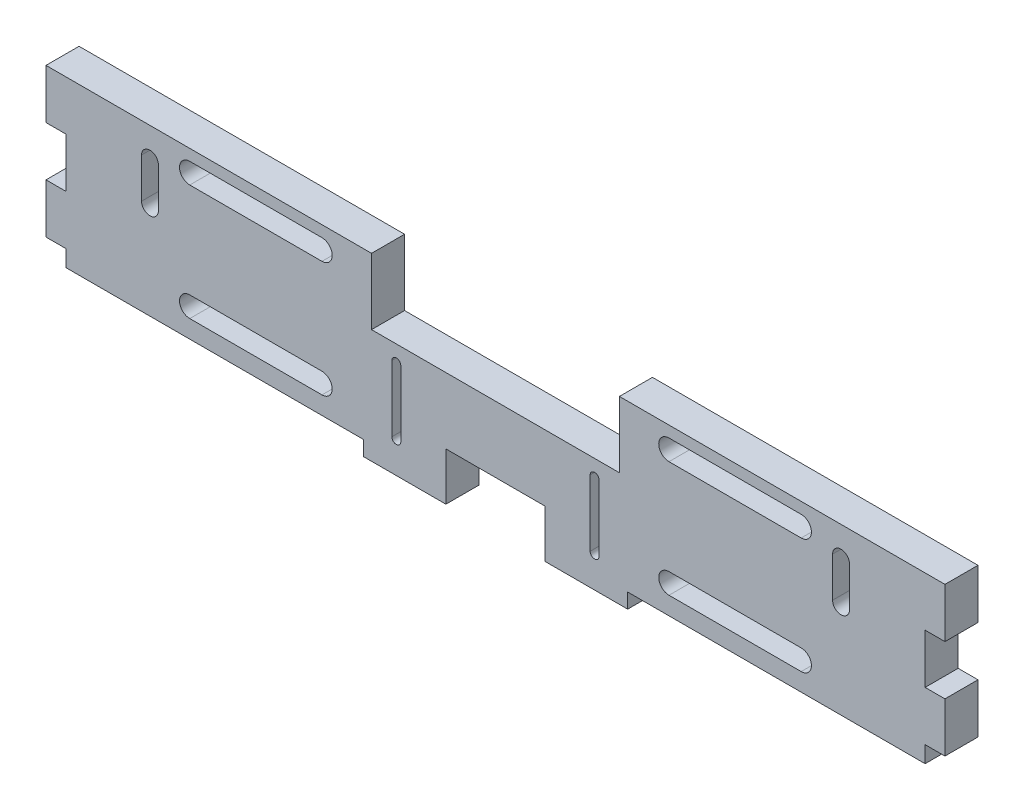
SolidWorks part; units mm, degrees
ref_plane "前基準面" through (0, 0, 0) normal (0, 0, 1) x (1, 0, 0)
ref_plane "上基準面" through (0, 0, 0) normal (0, 1, 0) x (1, 0, 0)
ref_plane "右基準面" through (0, 0, 0) normal (1, 0, 0) x (0, 0, -1)
sketch "草圖1" plane through (0, 0, 0) normal (0, 0, 1) x (1, 0, 0)
  line L0 (136, -22.5) -> (136, -7.5)
  line L1 (136, 22.5) -> (-136, 22.5)
  line L2 (130, 7.5) -> (130, -7.5)
  line L3 (130, -27.5) -> (-130, -27.5)
  line L4 (-130, 7.5) -> (-130, -7.5)
  line L5 (0, -27.5) -> (0, 22.5) construction
  line L6 (130, 0) -> (-130, 0) construction
  line L9 (-130, 7.5) -> (-136, 7.5)
  line L10 (-136, 22.5) -> (-136, 7.5)
  line L14 (-136, -22.5) -> (-136, -7.5)
  line L15 (130, -7.5) -> (136, -7.5)
  line L16 (130, 7.5) -> (136, 7.5)
  line L17 (136, 22.5) -> (136, 7.5)
  line L18 (-136, -22.5) -> (-130, -22.5)
  line L19 (-130, -22.5) -> (-130, -27.5)
  line L20 (-136, -7.5) -> (-130, -7.5)
  line L21 (130, -22.5) -> (130, -27.5)
  line L22 (130, -22.5) -> (136, -22.5)
  line L23 (-30, -22.5) -> (-30, -2.5) construction
  line L24 (-31.35, -22.5) -> (-31.35, -2.5)
  line L25 (-28.65, -22.5) -> (-28.65, -2.5)
  line L26 (30, -22.5) -> (30, -2.5) construction
  line L27 (31.35, -22.5) -> (31.35, -2.5)
  line L28 (28.65, -22.5) -> (28.65, -2.5)
  arc A0 (-31.35, -22.5) -> (-28.65, -22.5) centre (-30, -22.5) ccw
  arc A1 (-28.65, -2.5) -> (-31.35, -2.5) centre (-30, -2.5) ccw
  arc A2 (31.35, -22.5) -> (28.65, -22.5) centre (30, -22.5) cw
  arc A3 (28.65, -2.5) -> (31.35, -2.5) centre (30, -2.5) cw
  point P0 (0, 0)
  point P8 (0, 0)
  point P13 (-136, -15)
  point P14 (136, -15)
  point P24 (-30, -12.5)
  point P31 (30, -12.5)
  point P36 (0, 0)
  dimension "D8" = 1.35
  dimension "D1" = 260
  dimension "D2" = 6
  dimension "D3" = 15
  dimension "D4" = 6
  dimension "D5" = 50
  dimension "D6" = 5
  dimension "D7" = 20
  dimension "D9" = 5
  dimension "D10" = 30
extrude "填料-伸長1" add sketch "草圖1" along normal blind 10
sketch "草圖2" plane through (0, 0, 10) normal (0, 0, 1) x (1, 0, 0)
  line L0 (-92.5, 16) -> (-52.5, 16) construction
  line L1 (-92.5, 19.1) -> (-52.5, 19.1)
  line L2 (-92.5, 12.9) -> (-52.5, 12.9)
  line L3 (-92.5, -19) -> (-52.5, -19) construction
  line L4 (-92.5, -15.9) -> (-52.5, -15.9)
  line L5 (-92.5, -22.1) -> (-52.5, -22.1)
  line L6 (0, 61.8937) -> (0, -44.053) construction
  line L7 (-130, -27.5) -> (130, -27.5) construction
  line L8 (52.5, 16) -> (92.5, 16) construction
  line L9 (52.5, 19.1) -> (92.5, 19.1)
  line L10 (52.5, 12.9) -> (92.5, 12.9)
  line L11 (52.5, -19) -> (92.5, -19) construction
  line L12 (52.5, -15.9) -> (92.5, -15.9)
  line L13 (52.5, -22.1) -> (92.5, -22.1)
  arc A0 (-92.5, 19.1) -> (-92.5, 12.9) centre (-92.5, 16) ccw
  arc A1 (-52.5, 12.9) -> (-52.5, 19.1) centre (-52.5, 16) ccw
  arc A2 (-92.5, -15.9) -> (-92.5, -22.1) centre (-92.5, -19) ccw
  arc A3 (-52.5, -22.1) -> (-52.5, -15.9) centre (-52.5, -19) ccw
  arc A4 (52.5, 19.1) -> (52.5, 12.9) centre (52.5, 16) ccw
  arc A5 (92.5, 12.9) -> (92.5, 19.1) centre (92.5, 16) ccw
  arc A6 (52.5, -15.9) -> (52.5, -22.1) centre (52.5, -19) ccw
  arc A7 (92.5, -22.1) -> (92.5, -15.9) centre (92.5, -19) ccw
  point P2 (-72.5, 16)
  point P7 (-72.5, -19)
  point P22 (72.5, 16)
  point P27 (72.5, -19)
  point P37 (-95.6, -19)
  point P38 (49.4, -19)
  dimension "D3" = 3.1
  dimension "D1" = 35
  dimension "D2" = 5.4
  dimension "D4" = 40
  dimension "D6" = 145
  dimension "D5" = 2
extrude "除料-伸長1" cut sketch "草圖2" against normal through all
sketch "草圖3" plane through (0, 0, 10) normal (0, 0, 1) x (1, 0, 0)
  line L0 (0, 40.44) -> (0, -35.44) construction
  line L1 (-130, -27.5) -> (130, -27.5) construction
  line L2 (15, -17.5) -> (-15, -17.5)
  line L3 (15, -17.5) -> (15, -27.5)
  line L4 (15, -27.5) -> (-15, -27.5)
  line L5 (-15, -17.5) -> (-15, -27.5)
  line L6 (0, -27.5) -> (0, -17.5) construction
  line L7 (15, -22.5) -> (-15, -22.5) construction
  line L8 (136, 22.5) -> (-136, 22.5) construction
  line L9 (-37.5, 22.5) -> (37.5, 22.5)
  line L10 (-37.5, 22.5) -> (-37.5, 2.5)
  line L11 (-37.5, 2.5) -> (37.5, 2.5)
  line L12 (37.5, 22.5) -> (37.5, 2.5)
  circle A0 centre (0, 40.44) radius 36 construction
  point P3 (0, -22.5)
  point P16 (0, 2.5)
  point P30 (0, 0)
  point P31 (0, 0)
  dimension "D3" = 72
  dimension "D1" = 10
  dimension "D2" = 30
  dimension "D4" = 67.94
  dimension "D5" = 20
  dimension "D6" = 75
extrude "除料-伸長2" cut sketch "草圖3" against normal through all
sketch "草圖4" plane through (0, -27.5, 0) normal (0, -1, 0) x (1, 0, 0)
  line L0 (-130, 0) -> (-15, 0) construction
  line L1 (-15, 10) -> (-40, 10)
  line L2 (-15, 10) -> (-15, 0)
  line L3 (-15, 0) -> (-40, 0)
  line L4 (-40, 10) -> (-40, 0)
  line L5 (0, 39.3448) -> (0, -9.8344) construction
  line L6 (15, 0) -> (40, 0)
  line L7 (40, 10) -> (40, 0)
  line L8 (15, 10) -> (40, 10)
  line L9 (15, 10) -> (15, 0)
  dimension "D1" = 25
  dimension "D2" = 30
extrude "填料-伸長2" add sketch "草圖4" along normal blind 4.5
sketch "草圖5" plane through (0, 0, 10) normal (0, 0, 1) x (1, 0, 0)
  line L0 (-46.5, -27.5) -> (-98.5, -27.5) construction
  line L1 (-46.5, -27.5) -> (-46.5, 24.5) construction
  line L2 (-46.5, 24.5) -> (-98.5, 24.5) construction
  line L3 (-98.5, -27.5) -> (-98.5, 24.5) construction
  line L4 (-112.3, 7.4) -> (-99.5, 7.4) construction
  line L5 (-112.3, 20) -> (-99.5, 20) construction
  line L6 (-112.3, 20) -> (-112.3, -5.2) construction
  line L7 (-112.3, -5.2) -> (-99.5, -5.2) construction
  line L8 (-99.5, 20) -> (-99.5, -5.2) construction
  line L9 (-107.1, 13.45) -> (-107.1, 1.35)
  line L10 (-102, 1.35) -> (-102, 13.45)
  line L11 (0, 35.1152) -> (0, -35.1152) construction
  line L12 (107.1, 13.45) -> (107.1, 1.35)
  line L13 (102, 1.35) -> (102, 13.45)
  line L14 (-130, -27.5) -> (-40, -27.5) construction
  line L15 (-136, 22.5) -> (-136, 7.5) construction
  arc A0 (-102, 13.45) -> (-107.1, 13.45) centre (-104.55, 13.45) ccw
  arc A1 (-107.1, 1.35) -> (-102, 1.35) centre (-104.55, 1.35) ccw
  arc A2 (102, 13.45) -> (107.1, 13.45) centre (104.55, 13.45) cw
  arc A3 (107.1, 1.35) -> (102, 1.35) centre (104.55, 1.35) cw
  point P12 (-104.55, 3.9)
  point P13 (-104.55, 10.9)
  point P16 (-104.55, 16)
  point P18 (-107.1, 13.45)
  point P21 (-102, 13.45)
  dimension "D5" = 5.1
  dimension "D1" = 52
  dimension "D2" = 52
  dimension "D3" = 12.8
  dimension "D4" = 7
  dimension "D6" = 4
  dimension "D7" = 2.5
  dimension "D8" = 1
  dimension "D9" = 12.1
  dimension "D10" = 47.5
  dimension "D11" = 37.5
extrude "除料-伸長3" cut sketch "草圖5" against normal through all
